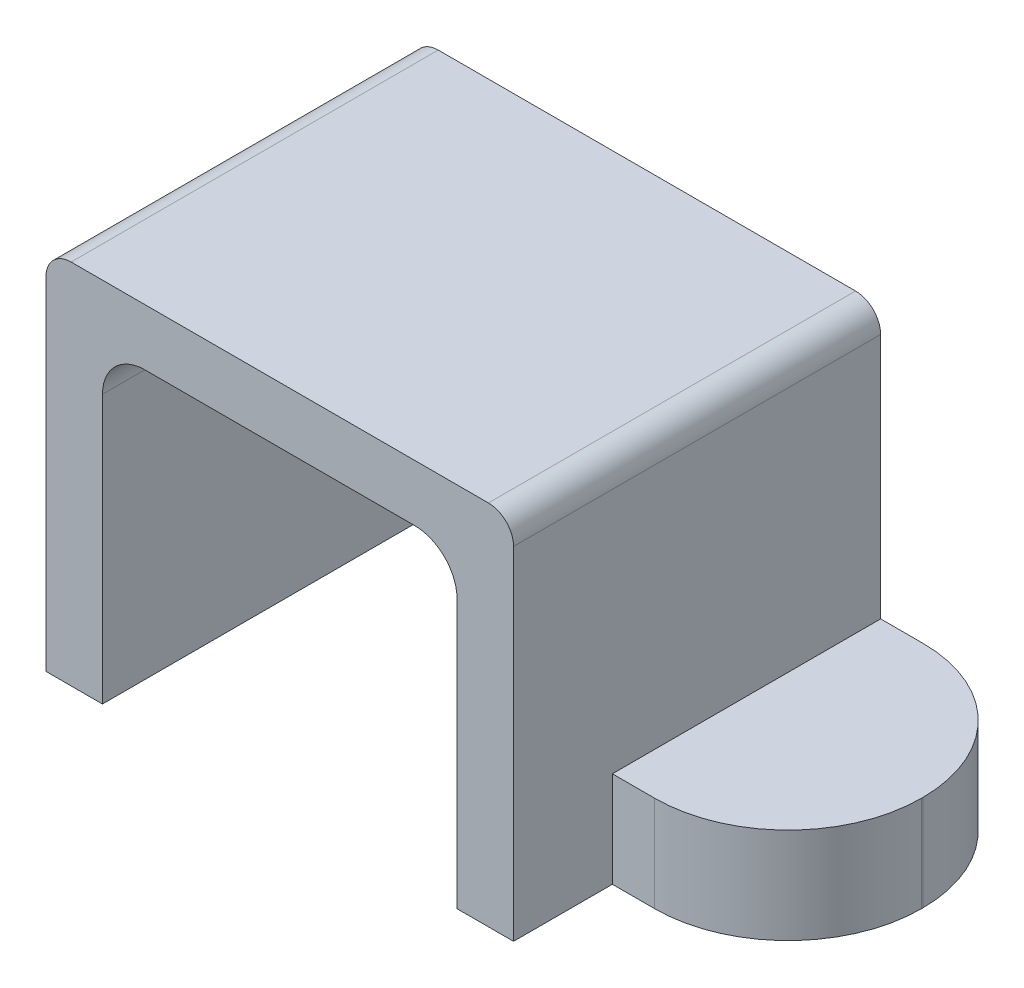
SolidWorks part; units mm, degrees
ref_plane "Přední rovina" through (0, 0, 0) normal (0, 0, 1) x (1, 0, 0)
ref_plane "Horní rovina" through (0, 0, 0) normal (0, 1, 0) x (1, 0, 0)
ref_plane "Pravá rovina" through (0, 0, 0) normal (1, 0, 0) x (0, 0, -1)
sketch "Skica1" plane through (0, 0, 0) normal (0, 0, 1) x (1, 0, 0)
  line L1 (-7.45, -5.85) -> (7.45, -5.85)
  line L2 (-7.45, -5.85) -> (-7.45, 5.85)
  line L3 (-7.45, 5.85) -> (7.45, 5.85)
  line L4 (7.45, -5.85) -> (7.45, 5.85)
  line L5 (-7.45, -5.85) -> (7.45, 5.85) construction
  line L6 (-7.45, 5.85) -> (7.45, -5.85) construction
  point P0 (0, 0)
  dimension "D1" = 11.7
  dimension "D2" = 14.9
extrude "Přidat vysunutím1" add sketch "Skica1" along normal blind 11.7
sketch "Skica2" plane through (0, 0, 11.7) normal (0, 0, 1) x (1, 0, 0)
  line L0 (-7.45, -5.85) -> (7.45, -5.85) construction
  line L1 (-5.65, -5.85) -> (5.65, -5.85)
  line L2 (-5.65, -5.85) -> (-5.65, 2.7)
  line L3 (-4.3, 4.05) -> (4.3, 4.05)
  line L4 (5.65, -5.85) -> (5.65, 2.7)
  line L5 (7.45, 5.85) -> (-7.45, 5.85) construction
  line L6 (-7.45, 5.85) -> (-7.45, -5.85) construction
  line L7 (7.45, -5.85) -> (7.45, 5.85) construction
  arc A0 (4.3, 4.05) -> (5.65, 2.7) centre (4.3, 2.7) cw
  arc A1 (-5.65, 2.7) -> (-4.3, 4.05) centre (-4.3, 2.7) cw
  point P6 (0, 5.85)
  dimension "D4" = 1.35
  dimension "D1" = 1.8
  dimension "D2" = 1.8
  dimension "D3" = 1.8
extrude "Odebrat vysunutím2" cut sketch "Skica2" against normal blind 2.3
sketch "Skica5" plane through (0, 0, 9.4) normal (0, 0, 1) x (1, 0, 0)
  line L0 (-4.3, 4.05) -> (4.3, 4.05)
  line L1 (5.65, -5.85) -> (5.65, 4.05)
  line L2 (5.65, 4.05) -> (4.3, 4.05)
  line L3 (-5.65, -5.85) -> (-5.65, 4.05)
  line L4 (-5.65, 4.05) -> (-4.3, 4.05)
  line L5 (-5.65, -5.85) -> (5.65, -5.85)
extrude "Odebrat vysunutím3" cut sketch "Skica5" against normal blind 20
fillet "Zaoblit2" radius 0.8 2 edges at (-7.45, 5.85, 5.85) (7.45, 5.85, 5.85)
sketch "Skica9" plane through (-7.45, 0, 0) normal (-1, 0, 0) x (0, 0, 1)
  line L1 (0, -5.85) -> (8.55, -5.85)
  line L2 (0, -5.85) -> (0, -2.8)
  line L3 (0, -2.8) -> (8.55, -2.8)
  line L4 (8.55, -5.85) -> (8.55, -2.8)
  dimension "D1" = 8.55
  dimension "D2" = 3.05
extrude "Přidat vysunutím3" add sketch "Skica9" along normal blind 5.6
fillet "Zaoblit3" radius 4.25 2 edges at (-13.05, -4.325, 8.55) (-13.05, -4.325, 0)
sketch "Skica10" plane through (7.45, 0, 0) normal (1, 0, 0) x (0, 0, -1)
  line L1 (0, -5.85) -> (-8.55, -5.85)
  line L2 (0, -5.85) -> (0, -2.8)
  line L3 (0, -2.8) -> (-8.55, -2.8)
  line L4 (-8.55, -5.85) -> (-8.55, -2.8)
  dimension "D1" = 3.05
  dimension "D2" = 8.55
extrude "Přidat vysunutím4" add sketch "Skica10" along normal blind 5.6 contours L3 L4 L1 L2
fillet "Zaoblit4" radius 4.25 2 edges at (13.05, -4.325, 0) (13.05, -4.325, 8.55)
